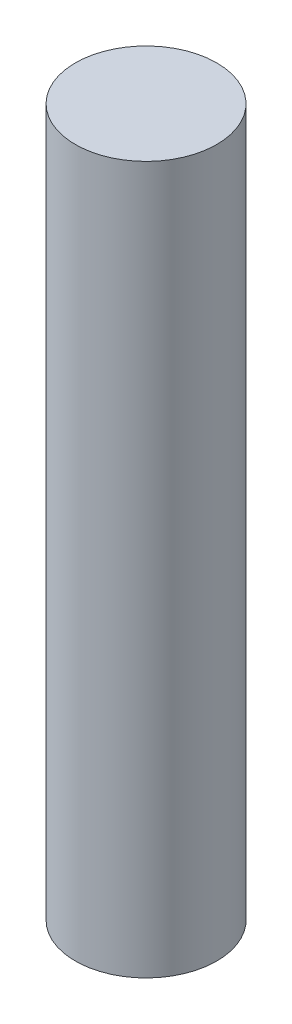
SolidWorks part; units mm, degrees
ref_plane "Front Plane" through (0, 0, 0) normal (0, 0, 1) x (1, 0, 0)
ref_plane "Top Plane" through (0, 0, 0) normal (0, 1, 0) x (1, 0, 0)
ref_plane "Right Plane" through (0, 0, 0) normal (1, 0, 0) x (0, 0, -1)
sketch "Sketch1" plane through (0, 0, 0) normal (0, 0, 1) x (1, 0, 0)
  line L0 (0, 0.4797) -> (25.4, 0.4797)
  line L2 (0, 0.4797) -> (0, 254.4797)
  line L3 (0, 254.4797) -> (25.4, 254.4797)
  line L4 (25.4, 0.4797) -> (25.4, 254.4797)
revolve "Revolve1" add sketch "Sketch1" angle 360 about L2
